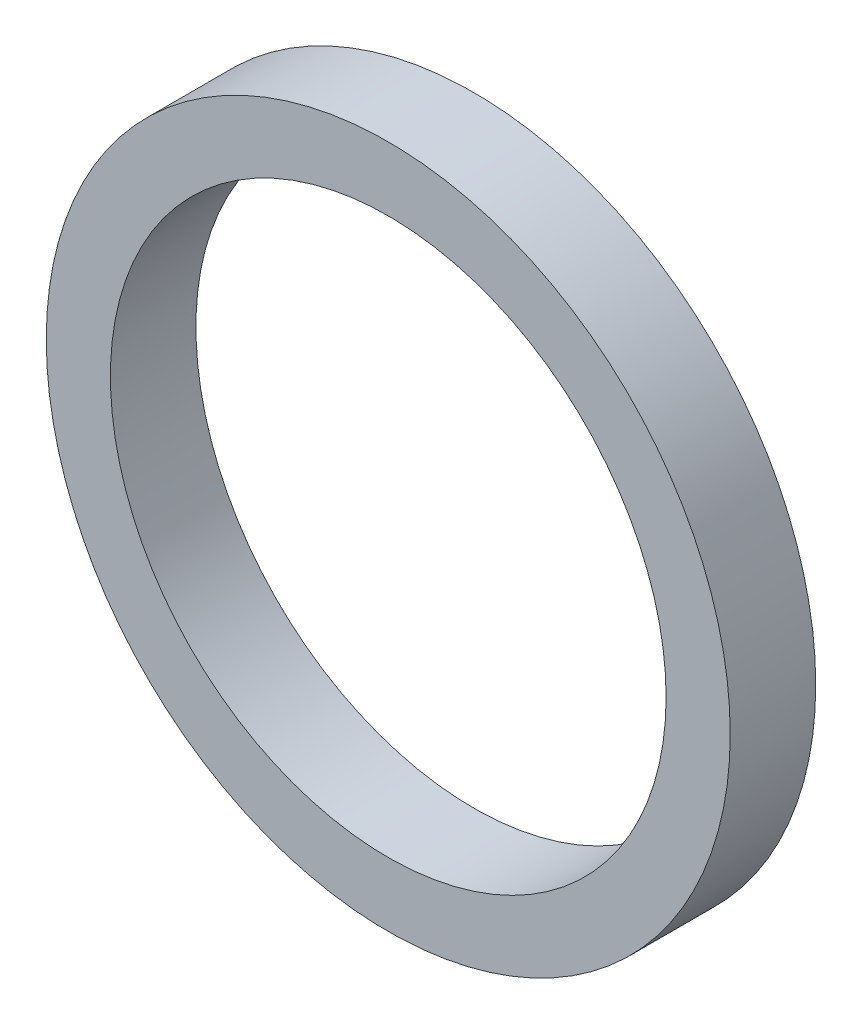
SolidWorks part; units mm, degrees
ref_plane "前视基准面" through (0, 0, 0) normal (0, 0, 1) x (1, 0, 0)
ref_plane "上视基准面" through (0, 0, 0) normal (0, 1, 0) x (1, 0, 0)
ref_plane "右视基准面" through (0, 0, 0) normal (1, 0, 0) x (0, 0, -1)
sketch "草图1" plane through (0, 0, 0) normal (0, 0, 1) x (1, 0, 0)
  circle A0 centre (0, 0) radius 32.5
  circle A2 centre (0, 0) radius 40
extrude "凸台-拉伸1" add sketch "草图1" along normal blind 10
